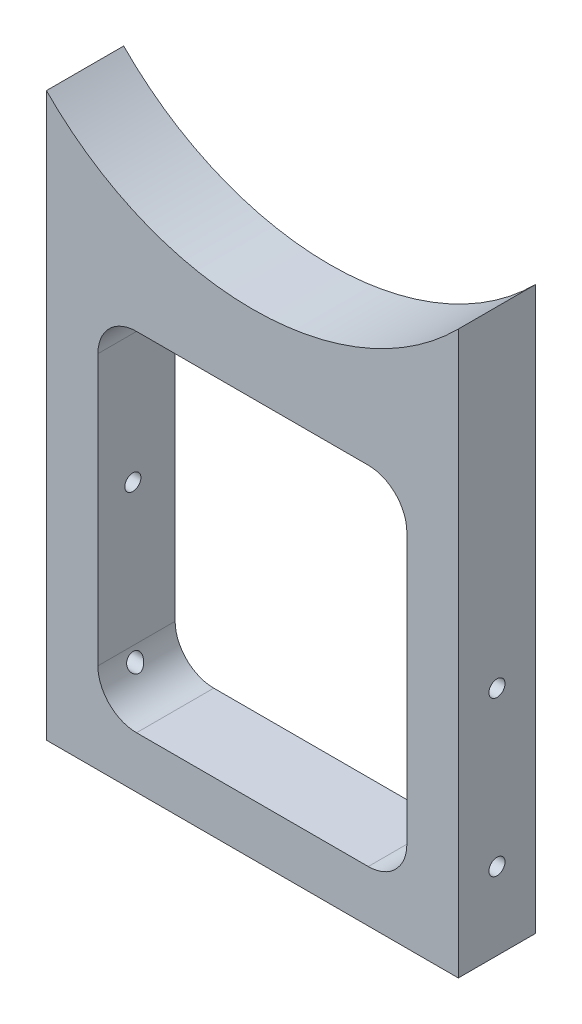
SolidWorks part; units mm, degrees
ref_plane "Plan de face" through (0, 0, 0) normal (0, 0, 1) x (1, 0, 0)
ref_plane "Plan de dessus" through (0, 0, 0) normal (0, 1, 0) x (1, 0, 0)
ref_plane "Plan de droite" through (0, 0, 0) normal (1, 0, 0) x (0, 0, -1)
sketch "Esquisse1" plane through (0, 0, 0) normal (0, 0, 1) x (1, 0, 0)
  line L0 (-9, -14.5) -> (9, -14.5)
  line L1 (-16, 18.5) -> (16, 18.5)
  line L2 (-16, 18.5) -> (-16, -18.5)
  line L3 (-16, -18.5) -> (16, -18.5)
  line L4 (16, 18.5) -> (16, -18.5)
  line L5 (-12, -11.5) -> (-12, 9.5)
  line L6 (12, -11.5) -> (12, 9.5)
  line L7 (-9, 12.5) -> (9, 12.5)
  line L8 (0, 18.5) -> (0.0191, 41) construction
  line L9 (-16, 18.5) -> (-16, 27.1775)
  line L10 (16, 18.5) -> (16, 27.1775)
  arc A0 (0, 18.5) -> (-16, 25.2) centre (0.0191, 41) cw
  arc A1 (0, 18.5) -> (16, 25.1614) centre (0.0191, 41) ccw
  arc A2 (12, -11.5) -> (9, -14.5) centre (9, -11.5) cw
  arc A3 (-12, -11.5) -> (-9, -14.5) centre (-9, -11.5) ccw
  arc A4 (9, 12.5) -> (12, 9.5) centre (9, 9.5) cw
  arc A5 (-9, 12.5) -> (-12, 9.5) centre (-9, 9.5) ccw
  point P4 (-12, -14.5)
  point P18 (12, -14.5)
  point P21 (-12, -14.5)
  point P26 (-12, 12.5)
  dimension "D11" = 3
  dimension "D1" = 37
  dimension "D2" = 32
  dimension "D3" = 16
  dimension "D4" = 18.5
  dimension "D5" = 4
  dimension "D6" = 4
  dimension "D7" = 27
  dimension "D8" = 24
  dimension "D9" = 22.5
  dimension "D10" = 22.5
  dimension "D12" = 43.7
extrude "Boss.-Extru.1" add sketch "Esquisse1" along normal blind 6 contours L1 A0 L9 | A1 L1 L10 | L4 L1 L2 L3 A5 L7 A4 L6 A2 L0 A3 L5
sketch "Esquisse3" plane through (16, 0, 0) normal (1, 0, 0) x (0, 0, -1)
  line L0 (-6, -18.5) -> (0, -18.5) construction
  line L1 (-6, 25.1614) -> (-6, -18.5) construction
  circle A0 centre (-3, -0.5) radius 0.625
  circle A1 centre (-3, -12.5) radius 0.625
  point P0 (-3, -12.5)
  point P5 (-3, -0.5)
  dimension "D5" = 1.25
  dimension "D6" = 1.25
  dimension "D1" = 6
  dimension "D2" = 3
  dimension "D3" = 18
  dimension "D4" = 3
extrude "Enlèv. mat.-Extru.4" cut sketch "Esquisse3" against normal blind 6
sketch "Esquisse4" plane through (-16, 0, 0) normal (-1, 0, 0) x (0, 0, 1)
  line L0 (6, -18.5) -> (0, -18.5) construction
  line L1 (0, -18.5) -> (0, 25.2) construction
  circle A0 centre (3.2848, -12.5) radius 0.625
  circle A1 centre (3.2848, -0.5) radius 0.625
  point P0 (3.2848, -12.5)
  point P8 (0, 0)
  dimension "D4" = 1.25
  dimension "D1" = 6
  dimension "D2" = 3.2848
  dimension "D5" = 18
  dimension "D3" = 2
extrude "Enlèv. mat.-Extru.5" cut sketch "Esquisse4" against normal blind 6
